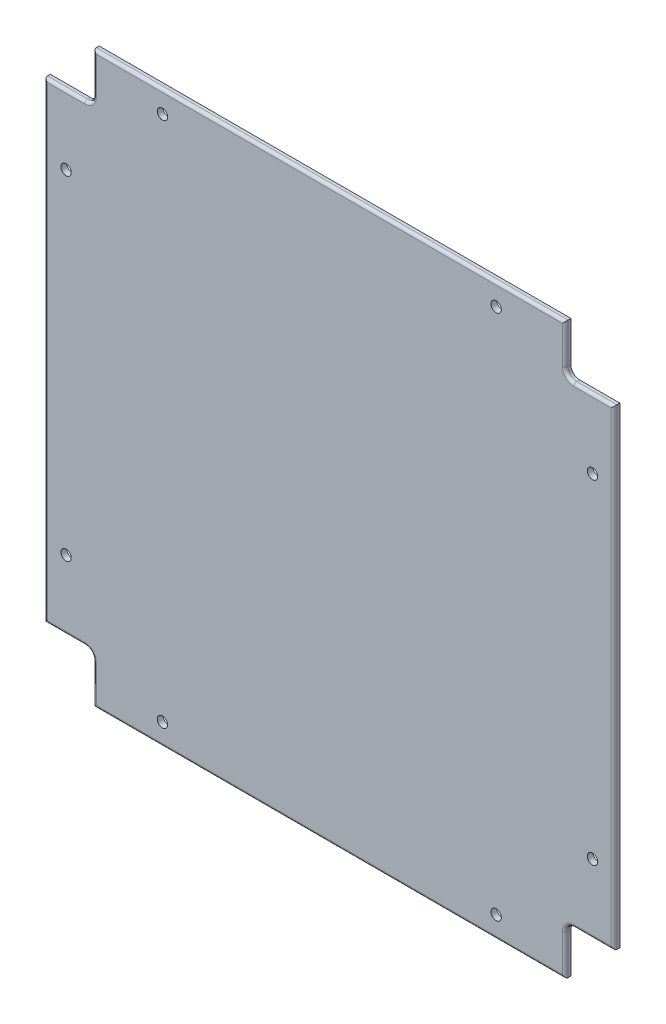
SolidWorks part; units mm, degrees
material "6061 Alloy"
ref_plane "Frontal" through (0, 0, 0) normal (0, 0, 1) x (1, 0, 0)
ref_plane "Superior" through (0, 0, 0) normal (0, 1, 0) x (1, 0, 0)
ref_plane "Direito" through (0, 0, 0) normal (1, 0, 0) x (0, 0, -1)
sketch "Sketch1" plane through (0, 0, 0) normal (0, 0, 1) x (1, 0, 0)
  line L1 (-49.5, -49.5) -> (49.5, -49.5)
  line L2 (-49.5, -49.5) -> (-49.5, 49.5)
  line L3 (-49.5, 49.5) -> (49.5, 49.5)
  line L4 (49.5, -49.5) -> (49.5, 49.5)
  line L5 (-49.5, -49.5) -> (49.5, 49.5) construction
  line L6 (-49.5, 49.5) -> (49.5, -49.5) construction
  point P0 (0, 0)
  dimension "D1" = 99
  dimension "D2" = 99
extrude "Boss-Extrude1" add sketch "Sketch1" along normal mid plane 1
sketch "Sketch2" plane through (0, 0, 0.5) normal (0, 0, 1) x (1, 0, 0)
  line L0 (-49.5, 49.5) -> (-49.5, -49.5) construction
  line L1 (-49.5, 49.5) -> (-41, 49.5)
  line L2 (-49.5, 49.5) -> (-49.5, 41)
  line L3 (-49.5, 41) -> (-42.5, 41)
  line L4 (-41, 49.5) -> (-41, 42.5)
  line L5 (49.5, 49.5) -> (41, 49.5)
  line L6 (49.5, 49.5) -> (49.5, 41)
  line L7 (49.5, 41) -> (42.5, 41)
  line L8 (41, 49.5) -> (41, 42.5)
  line L9 (-49.5, -49.5) -> (-41, -49.5)
  line L10 (-49.5, -49.5) -> (-49.5, -41)
  line L11 (-49.5, -41) -> (-42.5, -41)
  line L12 (-41, -49.5) -> (-41, -42.5)
  line L13 (49.5, -49.5) -> (41, -49.5)
  line L14 (49.5, -49.5) -> (49.5, -41)
  line L15 (49.5, -41) -> (42.5, -41)
  line L16 (41, -49.5) -> (41, -42.5)
  arc A0 (-41, 42.5) -> (-42.5, 41) centre (-42.5, 42.5) cw
  arc A1 (41, 42.5) -> (42.5, 41) centre (42.5, 42.5) ccw
  arc A2 (42.5, -41) -> (41, -42.5) centre (42.5, -42.5) ccw
  arc A3 (-42.5, -41) -> (-41, -42.5) centre (-42.5, -42.5) cw
  dimension "D1" = 1.5
  dimension "D3" = 1.5
  dimension "D5" = 1.5
  dimension "D7" = 1.5
  dimension "D2" = 8.5
  dimension "D4" = 8.5
  dimension "D6" = 8.5
  dimension "D8" = 8.5
  dimension "D9" = 8.5
  dimension "D10" = 8.5
  dimension "D11" = 8.5
  dimension "D12" = 8.5
extrude "Cut-Extrude1" cut sketch "Sketch2" against normal through all
hole_wizard "M1.6 Clearance Hole1" positions "Sketch4" profile "Sketch3" hole size "M1.6" standard "DIN"
sketch "Sketch4" plane through (0, 0, 0.5) normal (0, 0, 1) x (1, 0, 0)
  line L0 (-41, 42.5) -> (-41, 49.5) construction
  line L1 (41, 49.5) -> (-41, 49.5) construction
  line L2 (41, 49.5) -> (41, 42.5) construction
  line L3 (-49.5, 41) -> (-49.5, -41) construction
  line L4 (-49.5, 41) -> (-42.5, 41) construction
  line L5 (-42.5, -41) -> (-49.5, -41) construction
  line L6 (49.5, -41) -> (49.5, 41) construction
  line L7 (-41, -49.5) -> (41, -49.5) construction
  point P0 (-45.75, 29)
  point P2 (-29, 45.75)
  point P4 (29, 45.75)
  point P6 (45.75, 29)
  point P8 (45.75, -29)
  point P10 (29, -45.75)
  point P12 (-29, -45.75)
  point P14 (-45.75, -29)
  dimension "D1" = 12
  dimension "D2" = 3.75
  dimension "D3" = 12
  dimension "D4" = 3.75
  dimension "D5" = 12
  dimension "D6" = 12
  dimension "D7" = 3.75
  dimension "D8" = 3.75
sketch "Sketch3" plane through (-45.75, 29, 0.5) normal (1, 0, 0) x (0, -1, 0)
  line L0 (0, 0) -> (0, 3.5408)
  line L1 (0, 3.5408) -> (0.9, 3)
  line L2 (0.9, 3) -> (0.9, 0)
  line L5 (0.9, 0) -> (0, 0)
  line L10 (0, 3.5408) -> (-0.9, 3) construction
  line L11 (0, -6.35) -> (0, 107.95) construction
  dimension "Hole Dia." = 1.8
  dimension "Hole Depth" = 3
  dimension "Drill Angle" = 118
fillet "Fillet1" radius 0.5 16 edges at (41, 46, 0.5) (46, 41, 0.5) (49.5, 0, 0.5) (46, -41, 0.5) (41, -46, 0.5) (0, -49.5, 0.5) (-41, -46, 0.5) (-46, -41, 0.5) (-49.5, 0, 0.5) (-46, 41, 0.5) (-41, 46, 0.5) (0, 49.5, 0.5) (-41.4393, 41.4393, 0.5) (41.4393, 41.4393, 0.5) (41.4393, -41.4393, 0.5) (-41.4393, -41.4393, 0.5)
